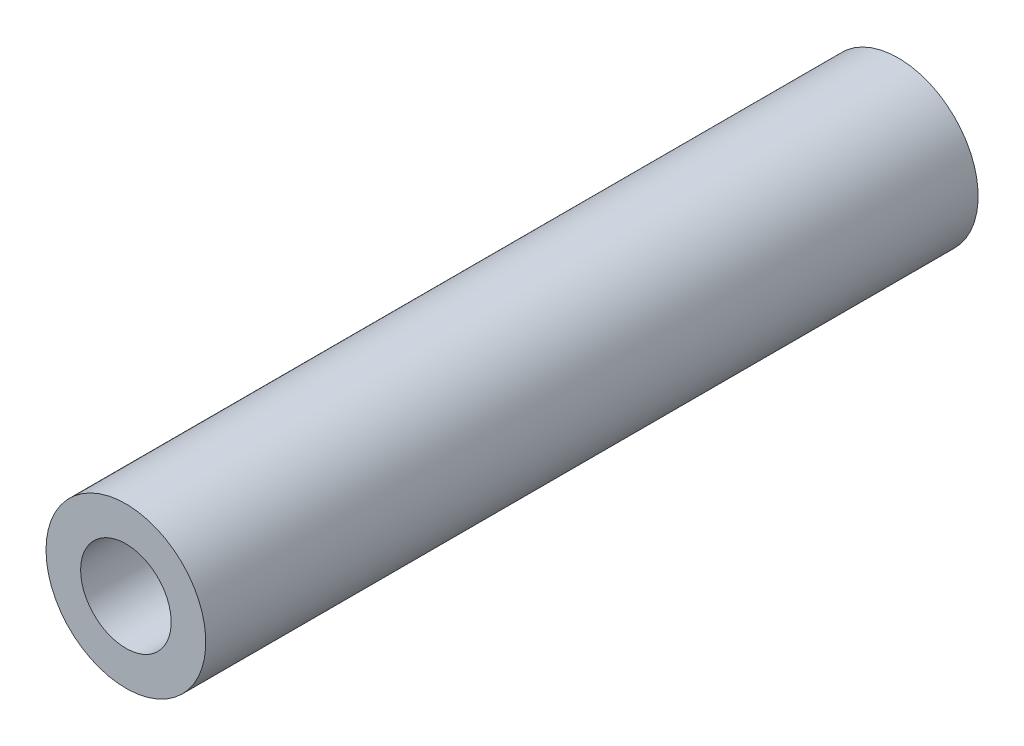
SolidWorks part; units mm, degrees
ref_plane "Front Plane" through (0, 0, 0) normal (0, 0, 1) x (1, 0, 0)
ref_plane "Top Plane" through (0, 0, 0) normal (0, 1, 0) x (1, 0, 0)
ref_plane "Right Plane" through (0, 0, 0) normal (1, 0, 0) x (0, 0, -1)
sketch "Sketch1" plane through (0, 0, 0) normal (0, 0, 1) x (1, 0, 0)
  circle A0 centre (0, 0) radius 3
  circle A1 centre (0, 0) radius 1.7
extrude "Ring_Envelope" add sketch "Sketch1" along normal blind 29
